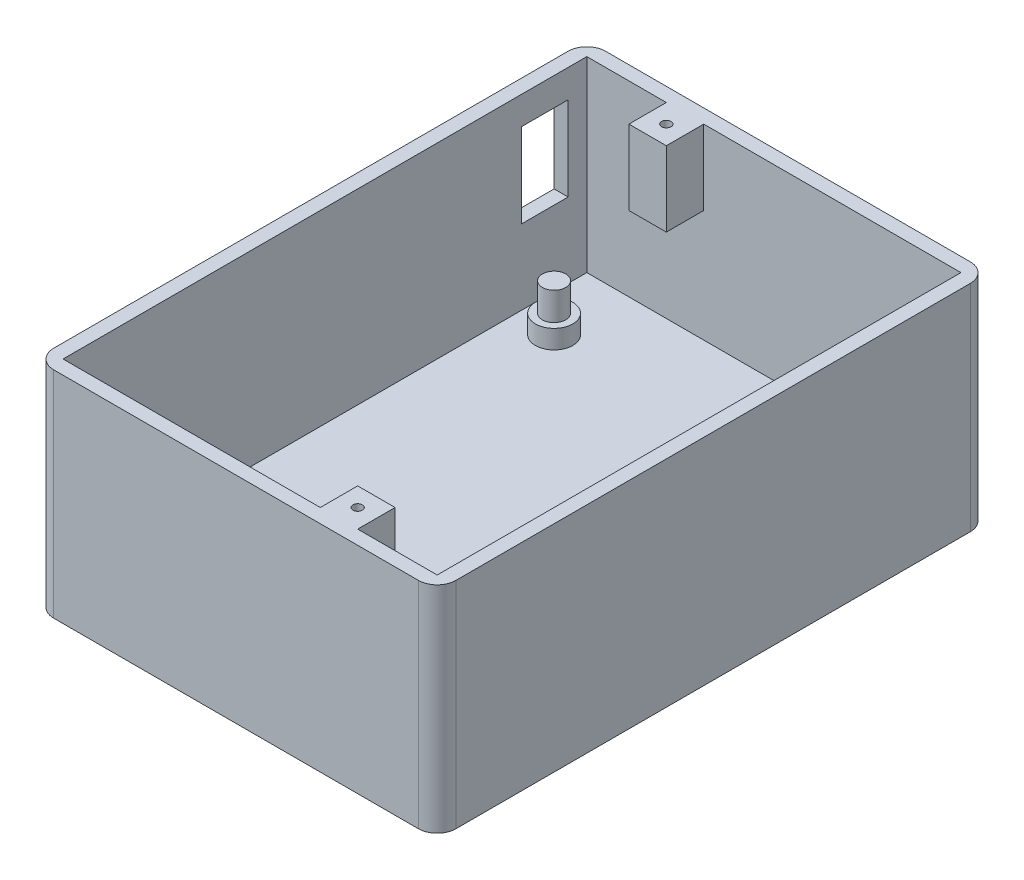
SolidWorks part; units mm, degrees
ref_plane "Alzado" through (0, 0, 0) normal (0, 0, 1) x (1, 0, 0)
ref_plane "Planta" through (0, 0, 0) normal (0, 1, 0) x (1, 0, 0)
ref_plane "Vista lateral" through (0, 0, 0) normal (1, 0, 0) x (0, 0, -1)
sketch "Croquis1" plane through (0, 0, 0) normal (0, 1, 0) x (1, 0, 0)
  line L0 (-20, 26.5) -> (20, 26.5) construction
  line L1 (-19.5, 29.5) -> (19.5, 29.5)
  line L2 (-21.5, 27.5) -> (-21.5, -27.5)
  line L3 (-19.5, -29.5) -> (19.5, -29.5)
  line L4 (21.5, 27.5) -> (21.5, -27.5)
  line L5 (20, 26.5) -> (20, -26.5) construction
  line L6 (20, -26.5) -> (-20, -26.5) construction
  line L7 (-20, -26.5) -> (-20, 26.5) construction
  arc A0 (19.5, 29.5) -> (21.5, 27.5) centre (19.5, 27.5) cw
  arc A1 (19.5, -29.5) -> (21.5, -27.5) centre (19.5, -27.5) ccw
  arc A2 (-19.5, -29.5) -> (-21.5, -27.5) centre (-19.5, -27.5) cw
  arc A3 (-19.5, 29.5) -> (-21.5, 27.5) centre (-19.5, 27.5) ccw
  point P4 (0, 29.5)
  point P6 (-21.5, 0)
  point P11 (0, 26.5)
  point P12 (20, 0)
  point P15 (21.5, 29.5)
  point P18 (21.5, -29.5)
  point P23 (-21.5, 29.5)
  dimension "D5" = 2
  dimension "D1" = 43
  dimension "D2" = 59
  dimension "D3" = 40
  dimension "D4" = 53
extrude "Saliente-Extruir1" add sketch "Croquis1" along normal blind 23
sketch "Croquis2" plane through (0, 23, 0) normal (0, 1, 0) x (1, 0, 0)
  line L1 (-20, 28) -> (20, 28)
  line L2 (-20, 28) -> (-20, -28)
  line L3 (-20, -28) -> (20, -28)
  line L4 (20, 28) -> (20, -28)
  point P4 (0, 28)
  point P6 (-20, 0)
  dimension "D1" = 40
  dimension "D2" = 56
extrude "Cortar-Extruir1" cut sketch "Croquis2" against normal blind 20
sketch "Croquis3" plane through (0, 3, 0) normal (0, 1, 0) x (1, 0, 0)
  line L0 (-20, 24) -> (6, 24) construction
  line L1 (6, 24) -> (6, -26) construction
  line L2 (6, -26) -> (-20, -26) construction
  line L3 (-20, -26) -> (-20, 24) construction
  line L4 (-19.5, 24) -> (-19.5, -26) construction
  line L7 (-20, -28) -> (20, -28) construction
  line L9 (-20, 28) -> (-20, -28) construction
  circle A0 centre (-16, 20.5) radius 2
  circle A1 centre (2, -22.5) radius 2
  dimension "D3" = 4
  dimension "D1" = 50
  dimension "D2" = 26
  dimension "D4" = 3.5
  dimension "D5" = 3.5
  dimension "D6" = 4
  dimension "D7" = 3.5
  dimension "D8" = 0.5
  dimension "D9" = 2
extrude "Saliente-Extruir2" add sketch "Croquis3" along normal blind 2 contours A0 | A1
sketch "Croquis4" plane through (0, 5, 0) normal (0, 1, 0) x (1, 0, 0)
  circle A0 centre (-16, 20.5) radius 1.25
  circle A1 centre (2, -22.5) radius 1.25
  dimension "D1" = 2.5
  dimension "D2" = 2.5
extrude "Saliente-Extruir3" add sketch "Croquis4" along normal blind 3
sketch "Croquis5" plane through (0, 0, -28) normal (0, 0, 1) x (1, 0, 0)
  line L0 (-20, 3) -> (-20, 23) construction
  line L1 (-11.5, 23) -> (-7.5, 23)
  line L2 (-11.5, 23) -> (-11.5, 15)
  line L3 (-11.5, 15) -> (-7.5, 15)
  line L4 (-7.5, 23) -> (-7.5, 15)
  line L5 (20, 23) -> (-20, 23) construction
  dimension "D1" = 8.5
  dimension "D2" = 8
  dimension "D3" = 4
extrude "Saliente-Extruir4" add sketch "Croquis5" along normal blind 4
sketch "Croquis6" plane through (0, 0, 28) normal (0, 0, -1) x (-1, 0, 0)
  line L0 (-20, 3) -> (-20, 23) construction
  line L1 (-11.5, 23) -> (-7.5, 23)
  line L2 (-11.5, 23) -> (-11.5, 15)
  line L3 (-11.5, 15) -> (-7.5, 15)
  line L4 (-7.5, 23) -> (-7.5, 15)
  line L5 (20, 23) -> (-20, 23) construction
  dimension "D1" = 8.5
  dimension "D2" = 8
  dimension "D3" = 4
extrude "Saliente-Extruir5" add sketch "Croquis6" along normal blind 4
sketch "Croquis7" plane through (0, 23, 0) normal (0, 1, 0) x (1, 0, 0)
  line L0 (-7.5, 24) -> (-7.5, 28) construction
  line L1 (-7.5, 24) -> (-11.5, 24) construction
  line L2 (7.5, -24) -> (11.5, -24) construction
  line L3 (11.5, -24) -> (11.5, -28) construction
  circle A0 centre (-9.5, 26) radius 0.5
  circle A1 centre (9.5, -26) radius 0.5
  point P8 (-7.5, 26)
  point P12 (-9.5, 24)
  point P16 (9.5, -24)
  point P20 (11.5, -26)
  dimension "D1" = 1
extrude "Cortar-Extruir2" cut sketch "Croquis7" against normal blind 7
sketch "Croquis9" plane through (-21.5, 0, 0) normal (-1, 0, 0) x (0, 0, 1)
  line L0 (-27.5, 23) -> (27.5, 23) construction
  line L1 (-26, 20) -> (-21, 20)
  line L2 (-26, 20) -> (-26, 11)
  line L3 (-26, 11) -> (-21, 11)
  line L4 (-21, 20) -> (-21, 11)
  line L5 (-27.5, 23) -> (-27.5, 0) construction
  dimension "D1" = 9
  dimension "D2" = 5
  dimension "D3" = 3
  dimension "D4" = 1.5
extrude "Cortar-Extruir3" cut sketch "Croquis9" against normal up to next
